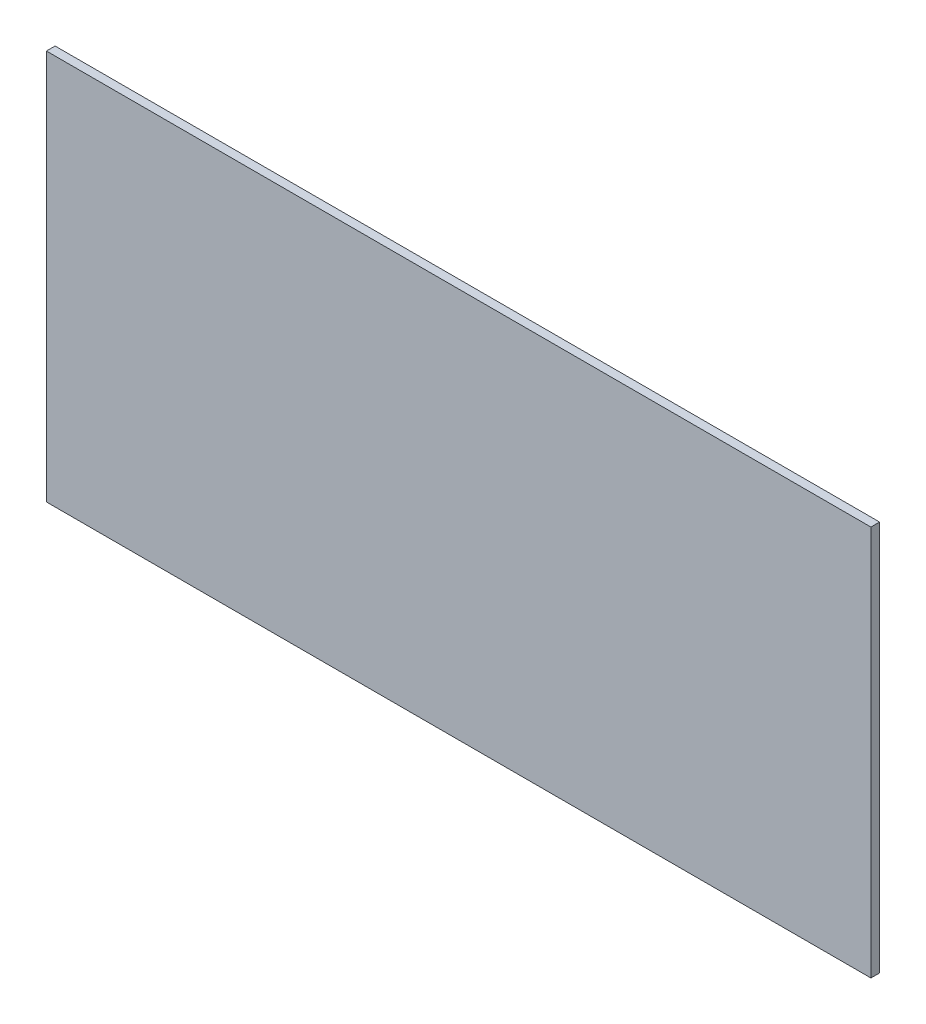
SolidWorks part; units mm, degrees
ref_plane "Front Plane" through (0, 0, 0) normal (0, 0, 1) x (1, 0, 0)
ref_plane "Top Plane" through (0, 0, 0) normal (0, 1, 0) x (1, 0, 0)
ref_plane "Right Plane" through (0, 0, 0) normal (1, 0, 0) x (0, 0, -1)
sketch "Sketch1" plane through (0, 0, 0) normal (0, 0, 1) x (1, 0, 0)
  line L1 (0, 0) -> (190, 0)
  line L2 (0, 0) -> (0, 90)
  line L3 (0, 90) -> (190, 90)
  line L4 (190, 0) -> (190, 90)
  dimension "D1" = 190
  dimension "D2" = 90
extrude "Profile" add sketch "Sketch1" along normal blind 2
equation "\"Profile_Depth\" = 2mm"
equation "\"D1@Profile\" = \"Profile_Depth\""
equation "\"Profile_Sketch_1\" = 190mm"
equation "\"D1@Sketch1\" = \"Profile_Sketch_1\""
equation "\"Profile_Sketch_2\" = 90mm"
equation "\"D2@Sketch1\" = \"Profile_Sketch_2\""
equation "\"EnvelopeWidth\" = 190mm"
equation "\"EnvelopeHeight\" = 90mm"
